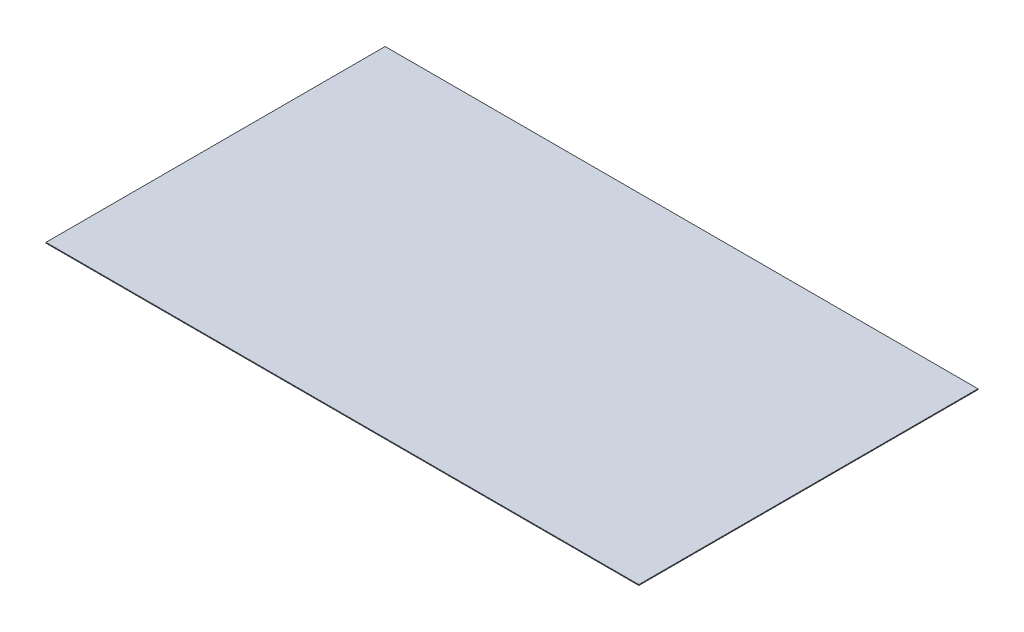
SolidWorks part; units mm, degrees
material "Plain Carbon Steel"
ref_plane "Front Plane" through (0, 0, 0) normal (0, 0, 1) x (1, 0, 0)
ref_plane "Top Plane" through (0, 0, 0) normal (0, 1, 0) x (1, 0, 0)
ref_plane "Right Plane" through (0, 0, 0) normal (1, 0, 0) x (0, 0, -1)
sketch "Sketch1" plane through (0, 0, 0) normal (0, 1, 0) x (1, 0, 0)
  line L1 (-1849.3982, -1057.9774) -> (1849.3982, -1057.9774)
  line L2 (-1849.3982, -1057.9774) -> (-1849.3982, 1057.9774)
  line L3 (-1849.3982, 1057.9774) -> (1849.3982, 1057.9774)
  line L4 (1849.3982, -1057.9774) -> (1849.3982, 1057.9774)
  line L5 (-1849.3982, -1057.9774) -> (1849.3982, 1057.9774) construction
  line L6 (-1849.3982, 1057.9774) -> (1849.3982, -1057.9774) construction
  point P0 (0, 0)
extrude "Boss-Extrude1" add sketch "Sketch1" along normal blind 5
